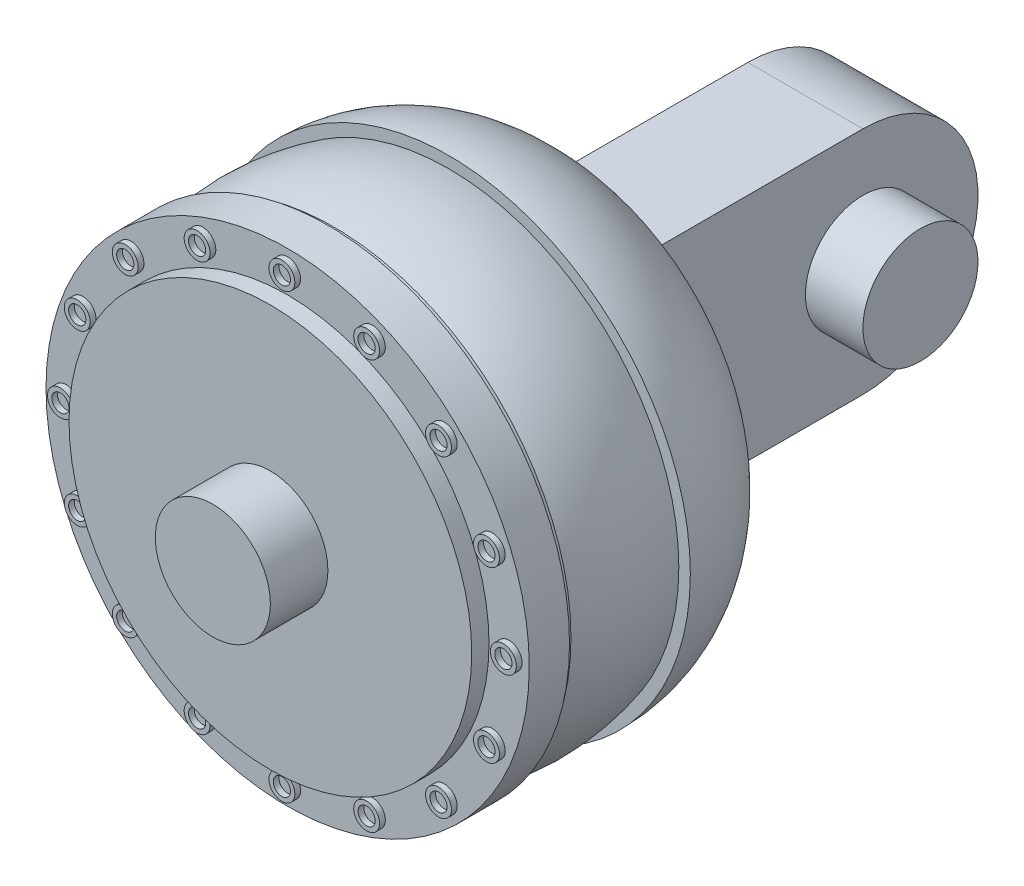
SolidWorks part; units mm, degrees
ref_plane "Front Plane" through (0, 0, 0) normal (0, 0, 1) x (1, 0, 0)
ref_plane "Top Plane" through (0, 0, 0) normal (0, 1, 0) x (1, 0, 0)
ref_plane "Right Plane" through (0, 0, 0) normal (1, 0, 0) x (0, 0, -1)
sketch "Sketch1" plane through (0, 0, 0) normal (0, 1, 0) x (1, 0, 0)
  line L0 (0, 0) -> (0, -20)
  line L1 (0, -20) -> (-42, -20)
  line L2 (-32, 0) -> (0, 0)
  arc A0 (-42, -20) -> (-32, 0) centre (-17, -20) cw
  dimension "D3" = 25
  dimension "D1" = 20
  dimension "D2" = 42
revolve "Revolve1" add sketch "Sketch1" angle 360 about L0
sketch "Sketch2" plane through (0, 0, 20) normal (0, 0, 1) x (1, 0, 0)
  circle A0 centre (0, 0) radius 39.5
  dimension "D1" = 79
extrude "Boss-Extrude2" add sketch "Sketch2" along normal blind 1
sketch "Sketch5" plane through (0, 0, 0) normal (0, 1, 0) x (1, 0, 0)
  line L0 (0, -20) -> (-40, -20)
  line L1 (-42, -20) -> (42, -20) construction
  line L2 (0, -20) -> (0, -40)
  line L3 (0, -40) -> (-40, -40)
  arc A0 (-40, -40) -> (-40, -20) centre (-4.377, -30) cw
  dimension "D3" = 37
  dimension "D1" = 40
  dimension "D2" = 20
revolve "Revolve2" add sketch "Sketch5" angle 360 about L2
sketch "Sketch6" plane through (0, 0, 40) normal (0, 0, 1) x (1, 0, 0)
  circle A0 centre (0, 0) radius 41.25
  dimension "D1" = 82.5
extrude "Boss-Extrude3" add sketch "Sketch6" along normal blind 1
sketch "Sketch7" plane through (0, 0, 41) normal (0, 0, 1) x (1, 0, 0)
  circle A0 centre (0, 0) radius 42
  dimension "D1" = 84
extrude "Boss-Extrude4" add sketch "Sketch7" along normal blind 7
sketch "Sketch8" plane through (0, 0, 48) normal (0, 0, 1) x (1, 0, 0)
  circle A0 centre (0, 0) radius 35
  dimension "D1" = 70
extrude "Boss-Extrude5" add sketch "Sketch8" along normal blind 3
sketch "Sketch9" plane through (0, 0, 48) normal (0, 0, 1) x (1, 0, 0)
  line L0 (35, 0) -> (42, 0)
  circle A0 centre (0, 0) radius 35 construction
  circle A1 centre (0, 0) radius 35 construction
  circle A2 centre (0, 0) radius 42 construction
  circle A3 centre (38.5, 0) radius 2.25
  circle A4 centre (38.5, 0) radius 1.5
  dimension "D1" = 4.5
  dimension "D2" = 3
extrude "Boss-Extrude6" add sketch "Sketch9" along normal blind 1 contours A4 L0 A3 | A4 L0 A3
pattern_circular "CirPattern1" count 16 over 360 about axis through (0, 0, 0) along (0, 0, 1) of "Boss-Extrude6"
sketch "Sketch10" plane through (0, 0, 0) normal (0, 0, -1) x (-1, 0, 0)
  line L1 (-10, 20) -> (10, 20)
  line L2 (-10, 20) -> (-10, -20)
  line L3 (-10, -20) -> (10, -20)
  line L4 (10, 20) -> (10, -20)
  line L5 (-10, 20) -> (10, -20) construction
  line L6 (-10, -20) -> (10, 20) construction
  point P0 (0, 0)
  dimension "D1" = 40
  dimension "D2" = 20
extrude "Boss-Extrude7" add sketch "Sketch10" along normal blind 42
sketch "Sketch11" plane through (-10, 0, 0) normal (-1, 0, 0) x (0, 0, 1)
  line L0 (-42, -20) -> (-42, 20) construction
  circle A0 centre (-42, 0) radius 20
extrude "Boss-Extrude8" add sketch "Sketch11" against normal up to surface (20 mm away) up to face at (10, 0, -21)
sketch "Sketch12" plane through (-10, 0, 0) normal (-1, 0, 0) x (0, 0, 1)
  circle A0 centre (-42, 0) radius 10
  dimension "D1" = 20
extrude "Boss-Extrude10" add sketch "Sketch12" along normal blind 10
sketch "Sketch13" plane through (0, 0, 51) normal (0, 0, 1) x (1, 0, 0)
  circle A0 centre (0, 0) radius 10
  dimension "D1" = 20
extrude "Boss-Extrude11" add sketch "Sketch13" along normal blind 10
sketch "Sketch14" plane through (10, 0, 0) normal (1, 0, 0) x (0, 0, -1)
  circle A0 centre (42, 0) radius 10
  dimension "D1" = 20
extrude "Boss-Extrude12" add sketch "Sketch14" along normal blind 10
